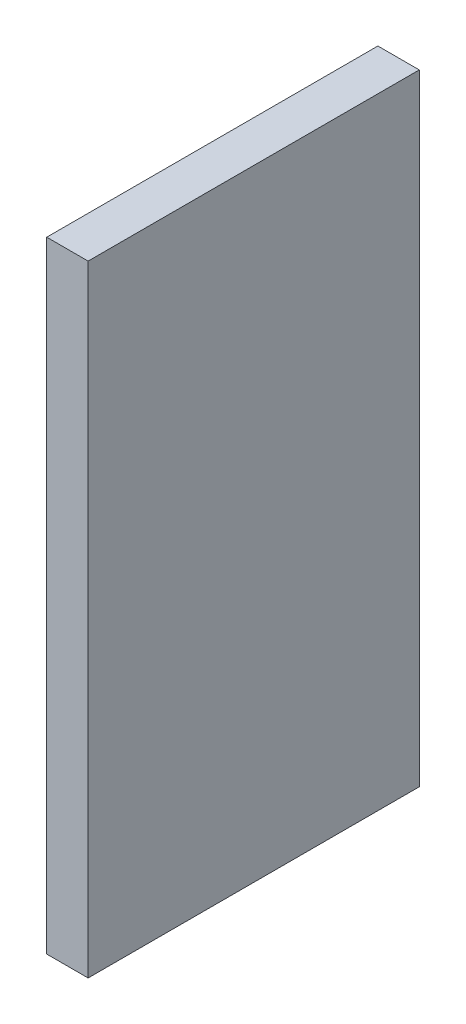
SolidWorks part; units mm, degrees
ref_plane "Face" through (0, 0, 0) normal (0, 0, 1) x (1, 0, 0)
ref_plane "Dessus" through (0, 0, 0) normal (0, 1, 0) x (1, 0, 0)
ref_plane "Droite" through (0, 0, 0) normal (1, 0, 0) x (0, 0, -1)
sketch "Esquisse1" plane through (0, 0, 0) normal (0, 0, 1) x (1, 0, 0)
  line L0 (2.5, 25.3071) -> (1.5, 25.3071)
  line L1 (1.5, 73.5868) -> (1.5, -27.4132) construction
  line L2 (2.5, 10.3071) -> (1.5, 10.3071)
  line L3 (1.5, 25.3071) -> (1.5, 10.3071)
  line L4 (2.5, 10.3071) -> (2.5, 25.3071) construction
  line L5 (2.5, 10.3071) -> (2.5, 25.3071)
extrude "Extrusion1" add sketch "Esquisse1" against normal blind 8
